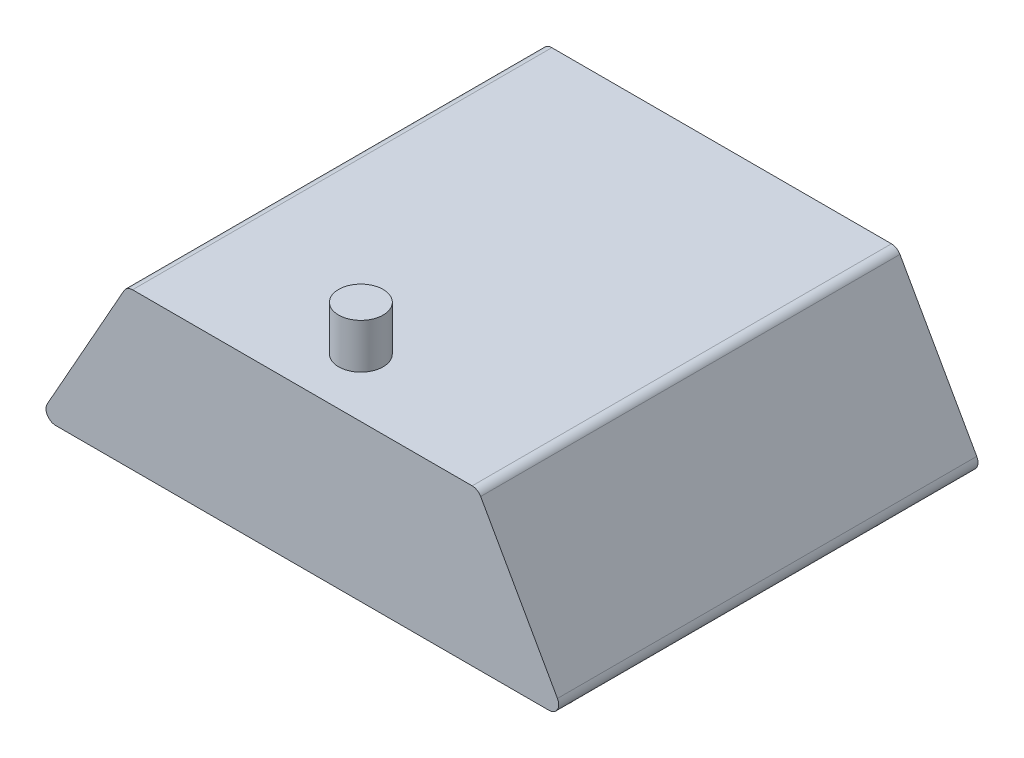
SolidWorks part; units mm, degrees
ref_plane "Front Plane" through (0, 0, 0) normal (0, 0, 1) x (1, 0, 0)
ref_plane "Top Plane" through (0, 0, 0) normal (0, 1, 0) x (1, 0, 0)
ref_plane "Right Plane" through (0, 0, 0) normal (1, 0, 0) x (0, 0, -1)
sketch "Sketch1" plane through (0, 0, 0) normal (0, 0, 1) x (1, 0, 0)
  line L0 (-126.4508, -40) -> (126.4508, -40)
  line L1 (-87.0758, 40) -> (87.0758, 40)
  line L2 (91.4336, 37.4513) -> (130.8086, -32.5487)
  line L3 (-91.4336, 37.4513) -> (-130.8086, -32.5487)
  arc A0 (-130.8086, -32.5487) -> (-126.4508, -40) centre (-126.4508, -35) ccw
  arc A1 (126.4508, -40) -> (130.8086, -32.5487) centre (126.4508, -35) ccw
  arc A2 (-91.4336, 37.4513) -> (-87.0758, 40) centre (-87.0758, 35) cw
  arc A3 (87.0758, 40) -> (91.4336, 37.4513) centre (87.0758, 35) cw
extrude "Boss-Extrude1" add sketch "Sketch1" along normal blind 215
sketch "Sketch2" plane through (0, 40, 0) normal (0, 1, 0) x (1, 0, 0)
  line L0 (0, -215) -> (0, -185)
  line L1 (87.0758, -215) -> (-87.0758, -215) construction
  circle A0 centre (0, -185) radius 11.405
  dimension "D2" = 22.81
  dimension "D1" = 30
extrude "Boss-Extrude2" add sketch "Sketch2" along normal blind 20
sketch "Sketch3" plane through (0, 40, 0) normal (0, 1, 0) x (1, 0, 0)
  circle A0 centre (0, -185) radius 11.405
sketch "Sketch4" plane through (0, -40, 0) normal (0, -1, 0) x (1, 0, 0)
  line L0 (0, 215) -> (0, 0)
  line L1 (-126.4508, 215) -> (126.4508, 215) construction
  line L3 (-100, 29.01) -> (100, 29.01)
  line L4 (-100, 29.01) -> (-100, 185.99)
  line L5 (-100, 185.99) -> (100, 185.99)
  line L6 (100, 29.01) -> (100, 185.99)
  line L7 (-100, 29.01) -> (100, 185.99) construction
  line L8 (-100, 185.99) -> (100, 29.01) construction
  circle A0 centre (-100, 185.99) radius 12.5
  circle A1 centre (100, 185.99) radius 12.5
  circle A2 centre (100, 29.01) radius 12.5
  circle A3 centre (-100, 29.01) radius 12.5
  point P5 (0, 107.5)
  dimension "D3" = 25
  dimension "D4" = 25
  dimension "D5" = 25
  dimension "D6" = 25
  dimension "D1" = 200
  dimension "D2" = 156.98
extrude "Boss-Extrude3" add sketch "Sketch4" along normal blind 20 draft 11 contours L4 A3 L3 | L3 A3 L4 | L5 A0 L4 | L4 A0 L5 | L6 A1 L5 | L5 A1 L6 | L3 A2 L6 | L6 A2 L3
sketch "Sketch5" plane through (0, 60, 0) normal (0, 1, 0) x (1, 0, 0)
  circle A0 centre (0, -185) radius 11.405
extrude "Boss-Extrude4" add sketch "Sketch5" along normal blind 3
